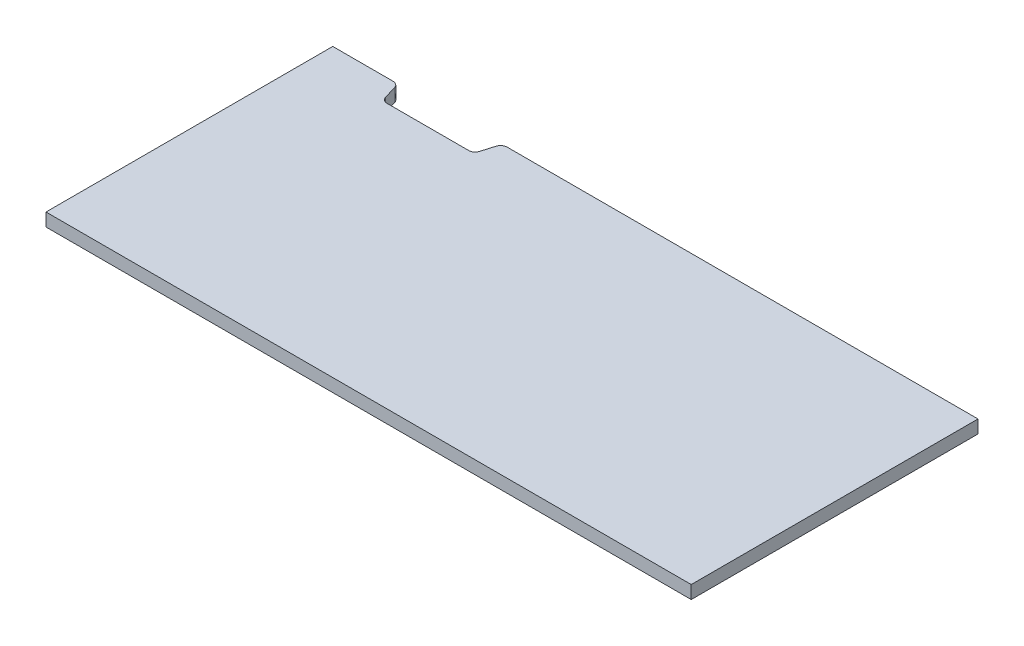
SolidWorks part; units mm, degrees
ref_plane "Front Plane" through (0, 0, 0) normal (0, 0, 1) x (1, 0, 0)
ref_plane "Top Plane" through (0, 0, 0) normal (0, 1, 0) x (1, 0, 0)
ref_plane "Right Plane" through (0, 0, 0) normal (1, 0, 0) x (0, 0, -1)
sketch "Sketch1" plane through (0, 0, 0) normal (0, 1, 0) x (1, 0, 0)
  line L1 (-314.325, -139.7) -> (314.325, -139.7)
  line L2 (-314.325, -139.7) -> (-314.325, 139.7)
  line L3 (-314.325, 139.7) -> (314.325, 139.7)
  line L4 (314.325, -139.7) -> (314.325, 139.7)
  line L5 (-314.325, -139.7) -> (314.325, 139.7) construction
  line L6 (-314.325, 139.7) -> (314.325, -139.7) construction
  point P0 (0, 0)
  dimension "D1" = 279.4
  dimension "D2" = 628.65
extrude "Boss-Extrude1" add sketch "Sketch1" along normal blind 12.7
sketch "Sketch2" plane through (0, 0, 0) normal (0, -1, 0) x (1, 0, 0)
  line L0 (-149.225, -139.7) -> (-250.825, -139.7)
  line L1 (314.325, -139.7) -> (-314.325, -139.7) construction
  line L2 (-250.825, -139.7) -> (-244.475, -118.11)
  line L3 (-244.475, -118.11) -> (-155.575, -118.11)
  line L4 (-155.575, -118.11) -> (-149.225, -139.7)
  line L5 (-200.025, -118.11) -> (-200.025, -139.7) construction
  dimension "D1" = 21.59
  dimension "D2" = 88.9
  dimension "D3" = 101.6
  dimension "D4" = 63.5
extrude "Cut-Extrude1" cut sketch "Sketch2" against normal through all
fillet "Fillet1" radius 6.35 4 edges at (-250.825, 6.35, -139.7) (-244.475, 6.35, -118.11) (-155.575, 6.35, -118.11) (-149.225, 6.35, -139.7)
